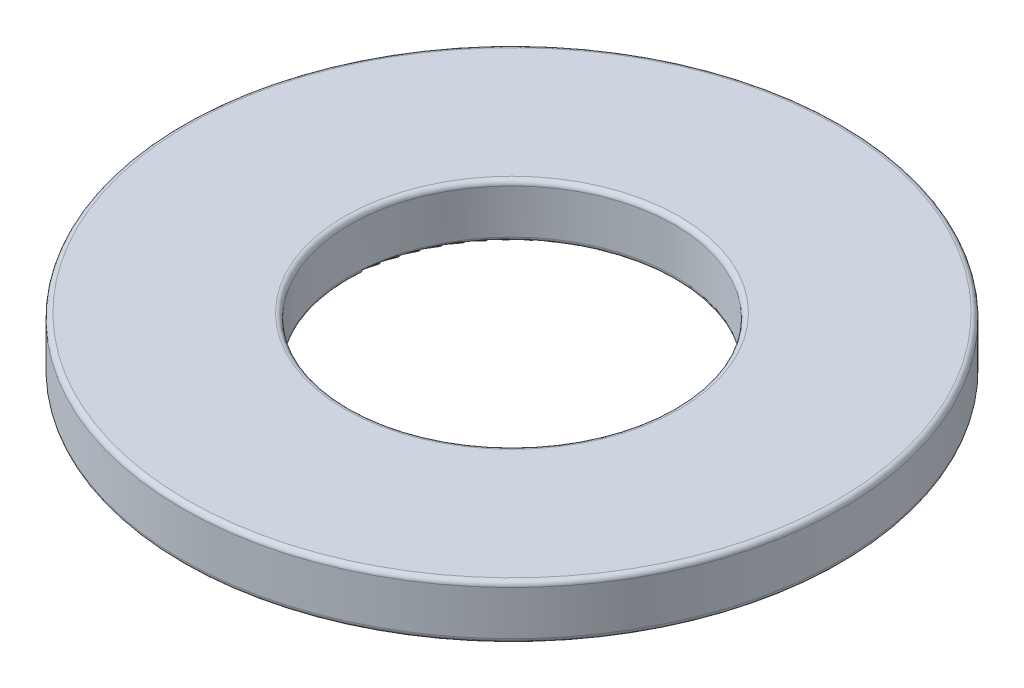
SolidWorks part; units mm, degrees
material "1023 Carbon Steel Sheet (SS)"
ref_plane "Front Plane" through (0, 0, 0) normal (0, 0, 1) x (1, 0, 0)
ref_plane "Top Plane" through (0, 0, 0) normal (0, 1, 0) x (1, 0, 0)
ref_plane "Right Plane" through (0, 0, 0) normal (1, 0, 0) x (0, 0, -1)
sketch "Sketch1" plane through (0, 0, 0) normal (0, 0, 1) x (1, 0, 0)
  line L0 (0, 0) -> (0, 66.6271) construction
  line L1 (1.65, 0) -> (3.35, 0)
  line L2 (3.35, 0) -> (3.35, 0.55)
  line L3 (3.35, 0.55) -> (1.65, 0.55)
  line L4 (1.65, 0.55) -> (1.65, 0)
  dimension "D1" = 3.3
  dimension "D2" = 6.7
  dimension "D3" = 0.55
revolve "Revolve1" add sketch "Sketch1" angle 360 about L0
fillet "Fillet1" radius 0.05 4 edges at (0, 0, -1.65) (0, 0.55, -1.65) (0, 0, -3.35) (0, 0.55, -3.35)
